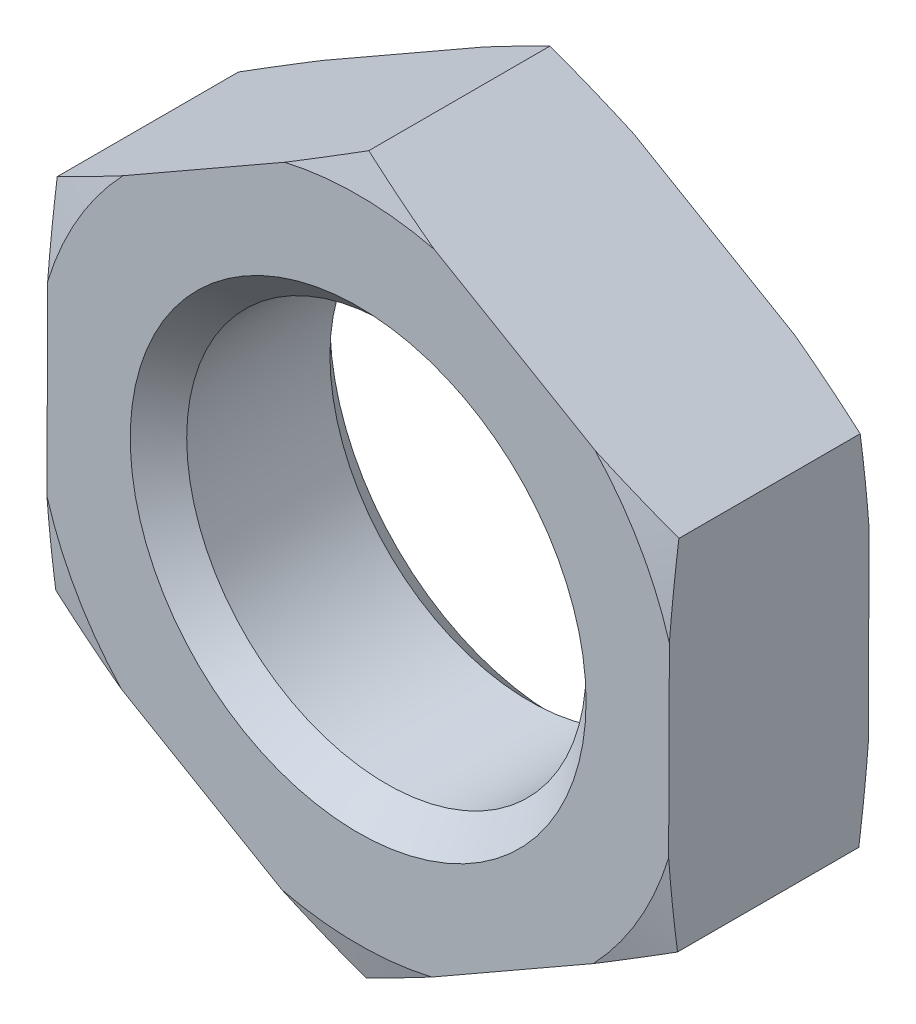
SolidWorks part; units mm, degrees
extrude "基体-拉伸" add sketch "草图1" along normal blind 4
sketch "草图1" plane through (0, 0, 0) normal (0, 0, 1) x (1, 0, 0)
  line L0 (-26.8088, 0) -> (37.1748, 0) construction
  line L1 (0, 25.0215) -> (0, -25.0215) construction
  line L3 (0.0283, 7.1899) -> (-6.2125, 3.6195)
  line L4 (-6.2125, 3.6195) -> (-6.2408, -3.5705)
  line L5 (-6.2408, -3.5705) -> (-0.0283, -7.1899)
  line L6 (-0.0283, -7.1899) -> (6.2125, -3.6195)
  line L7 (6.2125, -3.6195) -> (6.2408, 3.5705)
  line L8 (6.2408, 3.5705) -> (0.0283, 7.1899)
  circle A0 centre (0, 0) radius 6.2267 construction
  circle A1 centre (0, 0) radius 4
  dimension "D" = 8
  dimension "e" = 14.38
cosmetic thread "装饰螺纹线1"
chamfer "倒角1" distance 0.5655 angle 45 2 edges at (4, 0, 0) (4, 0, 4)
ref_plane "基准面1" through (0, 0, 0) normal (0, 0, 1) x (1, 0, 0)
ref_plane "基准面2" through (0, 0, 0) normal (0, 1, 0) x (1, 0, 0)
ref_plane "基准面3" through (0, 0, 0) normal (1, 0, 0) x (0, 0, -1)
sketch "尺寸草图" plane through (0, 0, 0) normal (0, 0, 1) x (1, 0, 0)
  line L0 (0, 0) -> (24.1005, 0)
  line L1 (27.4249, 65.7219) -> (36.1749, 65.7219)
  line L2 (46.8781, 65.7219) -> (58.4781, 65.7219)
  line L3 (-37.8187, 0) -> (-30.1996, 0)
  point P3 (8, 0)
  point P4 (1.5, 0)
  point P5 (14.38, 0)
  point P6 (4, 0)
  point P7 (24.32, 0)
  point P8 (13, 0)
  dimension "D" = 8
  dimension "e" = 14.38
  dimension "P" = 1.5
  dimension "m" = 4
  dimension "mw" = 24.32
  dimension "s" = 13
  dimension "da" = 8.75
  dimension "dw" = 11.6
  dimension "D1" = 7.619
sketch "草图2" plane through (0, 0, 0) normal (0, 0, -1) x (-1, 0, 0)
  circle A0 centre (0, 0) radius 6.5
  circle A1 centre (0, 0) radius 4 construction
  dimension "s" = 13
extrude "切除-拉伸1" cut sketch "草图2" against normal through all draft 75 flip side to cut
sketch "草图3" plane through (0, 0, 4) normal (0, 0, 1) x (1, 0, 0)
  circle A0 centre (0, 0) radius 6.5
  dimension "D1" = 13
extrude "切除-拉伸2" cut sketch "草图3" against normal through all draft 75 flip side to cut
equation "\"e@草图1\" = \"e@尺寸草图\""
equation "\"D1@尺寸草图\" = \"D@尺寸草图\" / 1.05"
equation "\"D@草图1\" = \"D@尺寸草图\""
equation "\"m@基体-拉伸\" = \"m@尺寸草图\""
equation "\"D1@草图3\" = \"s@尺寸草图\""
equation "\"s@草图2\" = \"s@尺寸草图\""
equation "\"D2@装饰螺纹线1\" = 1.05 * \"D1@尺寸草图\""
equation "\"D1@倒角1\" =  ( \"da@尺寸草图\" - \"D1@尺寸草图\" )  / 2"
